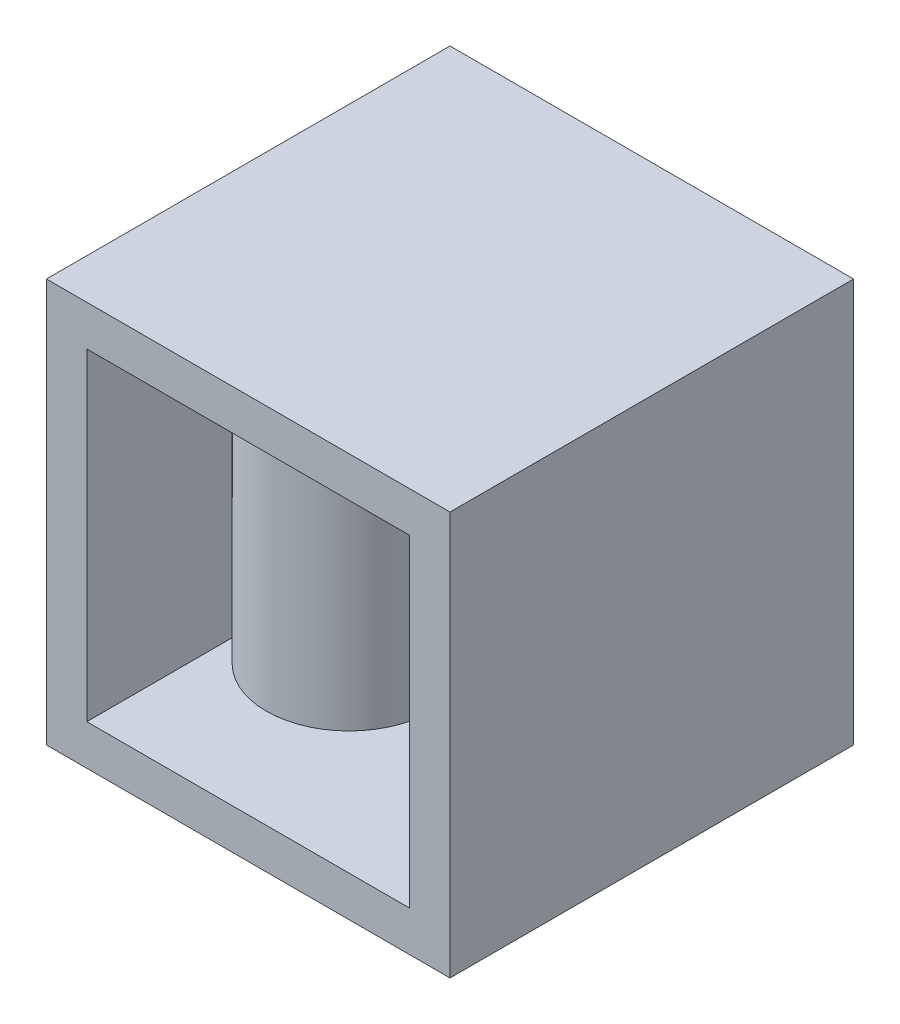
SolidWorks part; units mm, degrees
ref_plane "Front Plane" through (0, 0, 0) normal (0, 0, 1) x (1, 0, 0)
ref_plane "Top Plane" through (0, 0, 0) normal (0, 1, 0) x (1, 0, 0)
ref_plane "Right Plane" through (0, 0, 0) normal (1, 0, 0) x (0, 0, -1)
sketch "Sketch1" plane through (0, 0, 0) normal (0, 0, 1) x (1, 0, 0)
  line L1 (0, 0) -> (1000, 0)
  line L2 (0, 0) -> (0, 1000)
  line L3 (0, 1000) -> (1000, 1000)
  line L4 (1000, 0) -> (1000, 1000)
  line L5 (100, 900) -> (900, 900)
  line L6 (100, 900) -> (100, 100)
  line L7 (100, 100) -> (900, 100)
  line L8 (900, 900) -> (900, 100)
  dimension "D1" = 1000
  dimension "D2" = 1000
  dimension "D3" = 100
  dimension "D4" = 100
  dimension "D5" = 100
  dimension "D6" = 100
extrude "Boss-Extrude1" add sketch "Sketch1" along normal blind 1000 contours L1 L4 L3 L2 L5 L8 L7 L6
sketch "Sketch2" plane through (0, 900, 0) normal (0, -1, 0) x (1, 0, 0)
  line L0 (0, 1000) -> (1000, 1000) construction
  line L1 (0, 1000) -> (0, 0) construction
  circle A0 centre (500, 750) radius 205
  dimension "D1" = 410
  dimension "D2" = 250
  dimension "D3" = 500
extrude "Boss-Extrude2" add sketch "Sketch2" along normal blind 600
